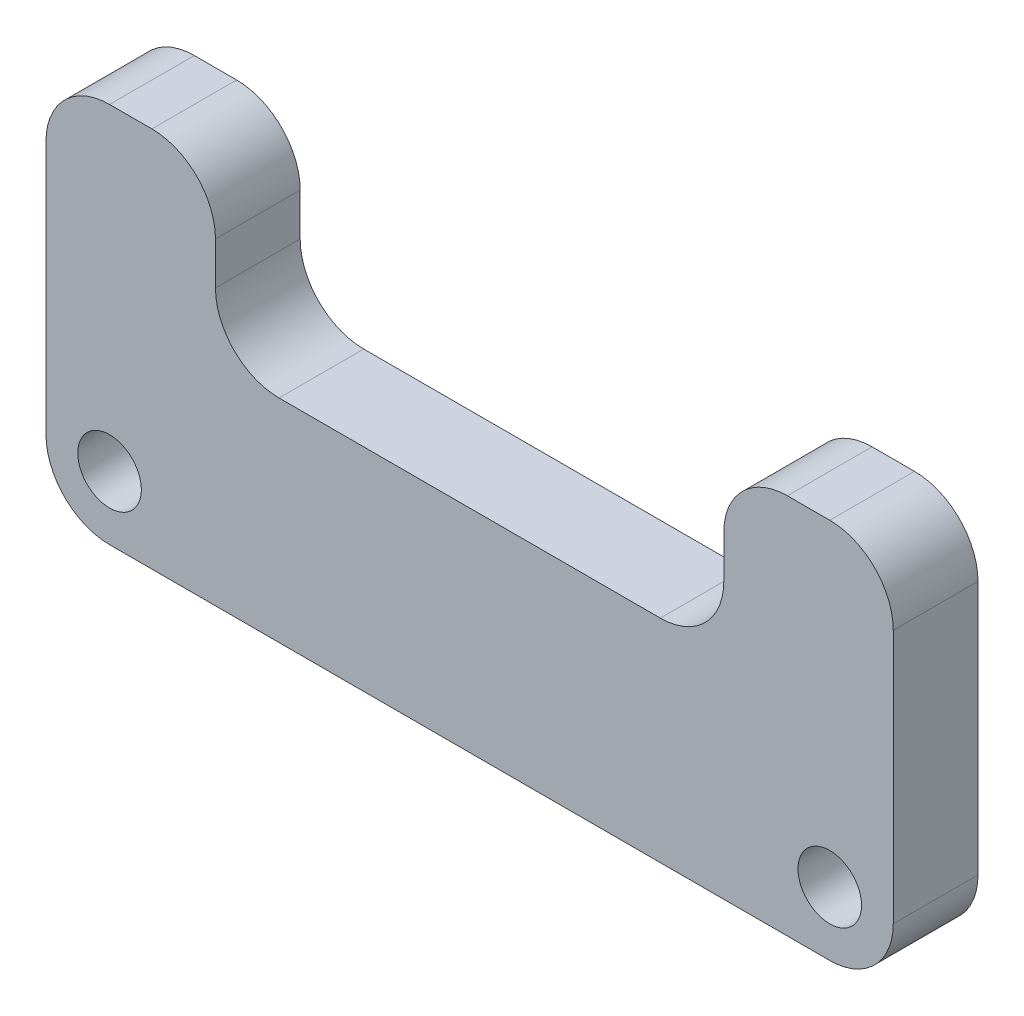
SolidWorks part; units mm, degrees
ref_plane "Front Plane" through (0, 0, 0) normal (0, 0, 1) x (1, 0, 0)
ref_plane "Top Plane" through (0, 0, 0) normal (0, 1, 0) x (1, 0, 0)
ref_plane "Right Plane" through (0, 0, 0) normal (1, 0, 0) x (0, 0, -1)
sketch "Sketch1" plane through (0, 0, 0) normal (0, 0, 1) x (1, 0, 0)
  line L0 (-85, 0) -> (85, 0)
  line L1 (100, 15) -> (100, 75)
  line L2 (85, 90) -> (75, 90)
  line L3 (60, 75) -> (60, 65)
  line L4 (45, 50) -> (-45, 50)
  line L5 (0, 103.9526) -> (0, -24.2476) construction
  line L6 (-60, 75) -> (-60, 65)
  line L7 (-85, 90) -> (-75, 90)
  line L8 (-100, 15) -> (-100, 75)
  arc A0 (60, 65) -> (45, 50) centre (45, 65) cw
  arc A1 (75, 90) -> (60, 75) centre (75, 75) ccw
  arc A2 (100, 75) -> (85, 90) centre (85, 75) ccw
  arc A3 (85, 0) -> (100, 15) centre (85, 15) ccw
  circle A4 centre (85, 15) radius 7.5
  circle A5 centre (-85, 15) radius 7.5
  arc A6 (-85, 0) -> (-100, 15) centre (-85, 15) cw
  arc A7 (-100, 75) -> (-85, 90) centre (-85, 75) cw
  arc A8 (-75, 90) -> (-60, 75) centre (-75, 75) cw
  arc A9 (-60, 65) -> (-45, 50) centre (-45, 65) ccw
  point P4 (0, 0)
  point P9 (-189.445, 145.3401)
  point P33 (0, 50)
  dimension "D1" = 15
  dimension "D2" = 15
  dimension "D3" = 15
  dimension "D4" = 15
  dimension "D5" = 15
extrude "Boss-Extrude1" add sketch "Sketch1" along normal blind 20
